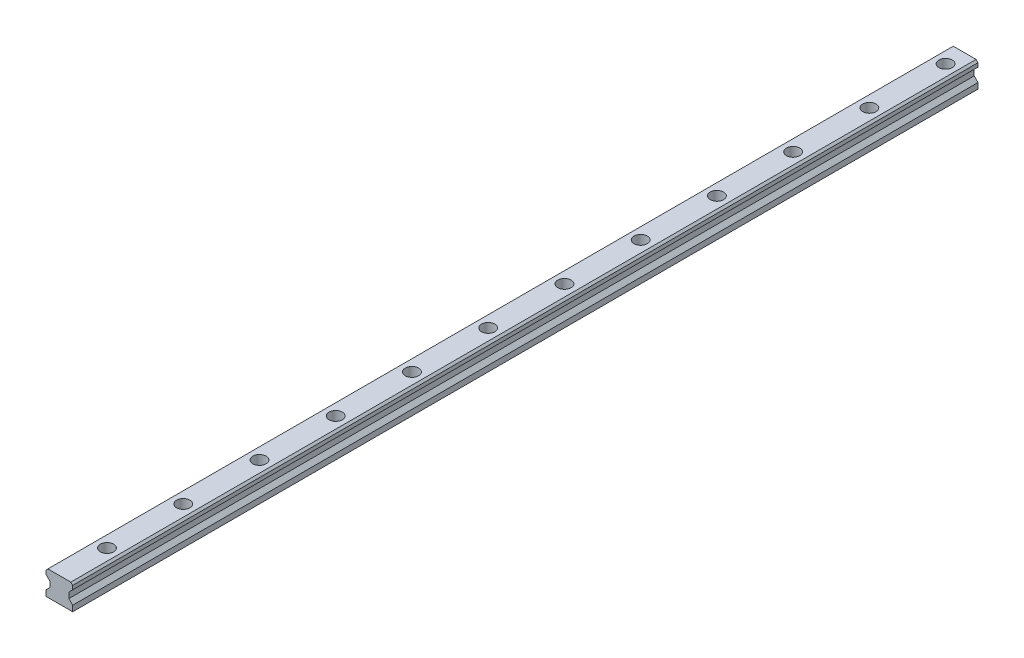
SolidWorks part; units mm, degrees
ref_plane "前视基准面" through (0, 0, 0) normal (0, 0, 1) x (1, 0, 0)
ref_plane "上视基准面" through (0, 0, 0) normal (0, 1, 0) x (1, 0, 0)
ref_plane "右视基准面" through (0, 0, 0) normal (1, 0, 0) x (0, 0, -1)
other "Configuration Table"
sketch "草图1" plane through (0, 0, 0) normal (0, 0, 1) x (1, 0, 0)
  line L0 (0, 45.0632) -> (0, -23.6584) construction
  line L1 (-14, 0) -> (14, 0)
  line L2 (14, 0) -> (14, 6)
  line L3 (14, 6) -> (10, 10)
  line L4 (10, 10) -> (10, 16)
  line L5 (10, 16) -> (14, 20)
  line L6 (14, 20) -> (14, 26)
  line L7 (14, 26) -> (-14, 26)
  line L8 (-14, 20) -> (-14, 26)
  line L9 (-10, 16) -> (-14, 20)
  line L10 (-10, 10) -> (-10, 16)
  line L11 (-14, 6) -> (-10, 10)
  line L12 (-14, 0) -> (-14, 6)
  point P12 (0, 26)
  point P17 (0, 0)
  dimension "D1" = 26
  dimension "D2" = 14
  dimension "D3" = 6
  dimension "D4" = 6
  dimension "D5" = 135
  dimension "D6" = 135
  dimension "D7" = 4
extrude "凸台-拉伸1" add sketch "草图1" along normal blind 950
chamfer "倒角1" distance 2 angle 45 2 edges at (-14, 26, 475) (14, 26, 475)
sketch "草图2" plane through (0, 26, 0) normal (0, 1, 0) x (1, 0, 0)
  line L0 (0, 0) -> (0, -52.6373) construction
  line L1 (12, 0) -> (-12, 0) construction
  circle A0 centre (0, -20) radius 7
  dimension "D1" = 14
  dimension "D2" = 20
extrude "切除-拉伸1" cut sketch "草图2" against normal blind 12
pattern_linear "阵列(线性)1" count 12 spacing 80 along (0, 0, 1) of "切除-拉伸1"
sketch "草图3" plane through (0, 26, 0) normal (0, 1, 0) x (1, 0, 0)
  circle A0 centre (0, -20) radius 4.5
  dimension "D1" = 9
extrude "切除-拉伸2" cut sketch "草图3" against normal blind 40
pattern_linear "阵列(线性)2" count 12 spacing 80 along (0, 0, 1) of "切除-拉伸2"
